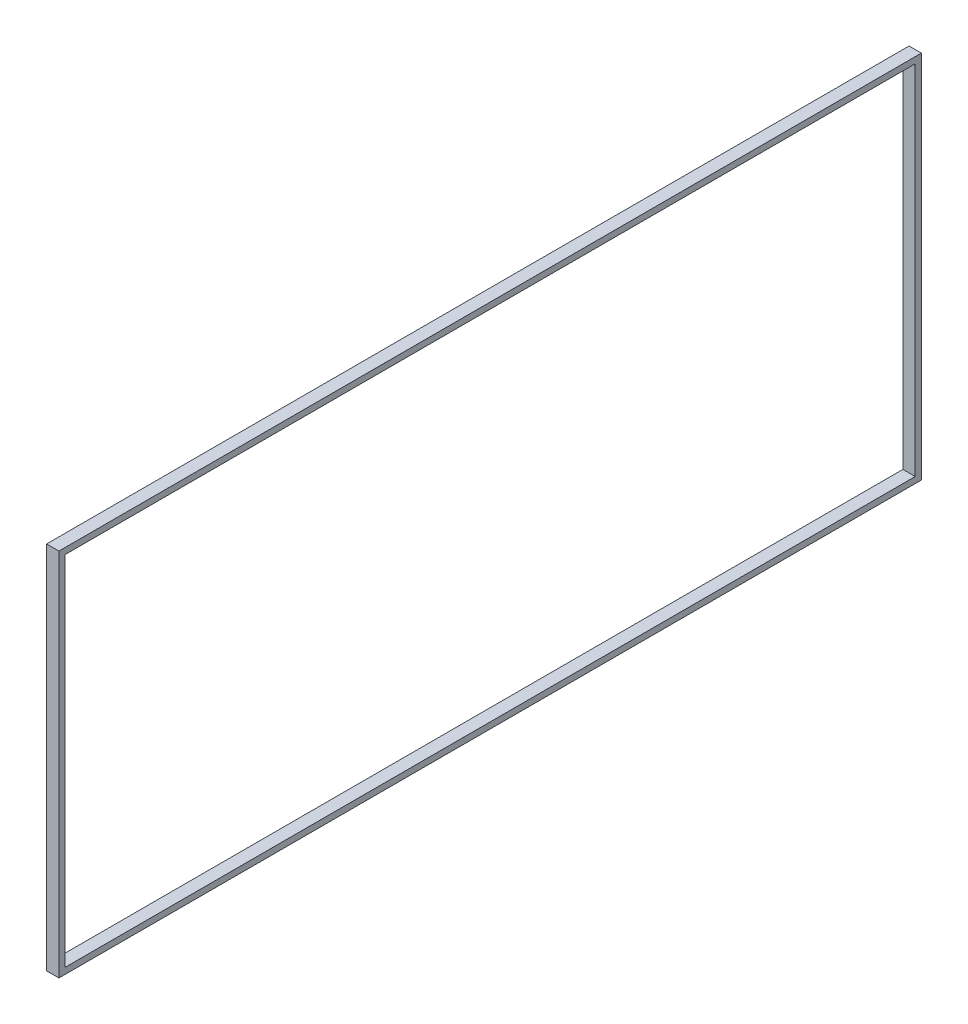
SolidWorks part; units mm, degrees
ref_plane "Front Plane" through (0, 0, 0) normal (0, 0, 1) x (1, 0, 0)
ref_plane "Top Plane" through (0, 0, 0) normal (0, 1, 0) x (1, 0, 0)
ref_plane "Right Plane" through (0, 0, 0) normal (1, 0, 0) x (0, 0, -1)
other "STL Graphics1"
ref_plane "Plane1" through (1477.78, 0, 0) normal (1, 0, 0) x (0, 0, -1)
sketch "Sketch1" plane through (1477.78, 0, 0) normal (1, 0, 0) x (0, 0, -1)
  line L1 (-3628.07, 2026.9174) -> (3373.8536, 2026.9174)
  line L2 (-3628.07, 2026.9174) -> (-3628.07, -974.9882)
  line L3 (-3628.07, -974.9882) -> (3373.8536, -974.9882)
  line L4 (3373.8536, 2026.9174) -> (3373.8536, -974.9882)
  line L5 (3323.8536, 1976.9174) -> (-3578.07, 1976.9174)
  line L6 (3323.8536, 1976.9174) -> (3323.8536, -924.9882)
  line L7 (3323.8536, -924.9882) -> (-3578.07, -924.9882)
  line L8 (-3578.07, 1976.9174) -> (-3578.07, -924.9882)
  dimension "D1" = 50
  dimension "D2" = 50
  dimension "D3" = 50
  dimension "D4" = 50
  dimension "D5" = 2026.9174
  dimension "D6" = 3373.8536
extrude "Boss-Extrude1" add sketch "Sketch1" along normal blind 100
